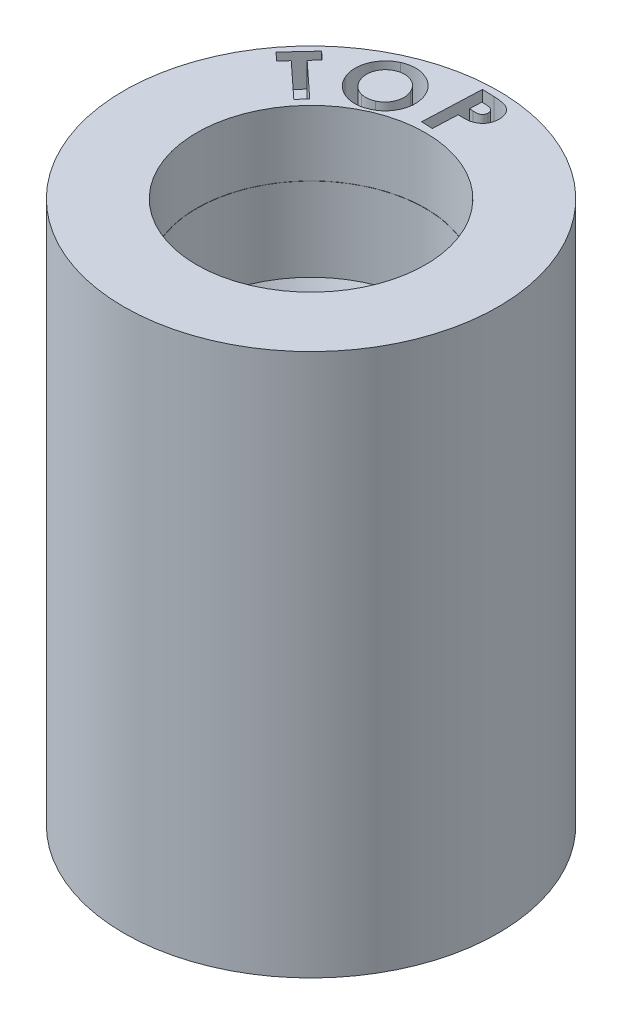
SolidWorks part; units mm, degrees
ref_plane "Front Plane" through (0, 0, 0) normal (0, 0, 1) x (1, 0, 0)
ref_plane "Top Plane" through (0, 0, 0) normal (0, 1, 0) x (1, 0, 0)
ref_plane "Right Plane" through (0, 0, 0) normal (1, 0, 0) x (0, 0, -1)
sketch "Sketch1" plane through (0, 0, 0) normal (0, 0, 1) x (1, 0, 0)
  line L0 (-5.7256, 16.593) -> (-5.7256, 0)
  line L1 (-5.7256, 0) -> (-2.5, 0)
  line L2 (-2.5, 0) -> (-2.5, 1)
  line L3 (-2.5, 1) -> (-4.7256, 1) construction
  line L4 (-4.7256, 1) -> (-4.7256, 4) construction
  line L5 (-4.7256, 4) -> (-1.9155, 1.1898) construction
  line L6 (-1.9155, 1.1898) -> (-4.7256, 7.007) construction
  line L7 (-4.7256, 7.007) -> (-4.7256, 8.007) construction
  line L8 (-4.7256, 8.007) -> (-2.0655, 5.3468) construction
  line L9 (-2.0655, 5.3468) -> (-4.7256, 10.8535) construction
  line L10 (-4.7256, 10.8535) -> (-4.7256, 11.8535) construction
  line L11 (-4.7256, 11.8535) -> (-2.1655, 9.2933) construction
  line L12 (-4.7256, 8.007) -> (-4.7256, 10.8535) construction
  line L13 (-4.7256, 4) -> (-4.7256, 7.007) construction
  line L14 (-2.1655, 9.2933) -> (-4.7256, 14.593) construction
  line L15 (-4.7256, 14.593) -> (-4.7256, 16.593) construction
  line L16 (-2.85, 2.1244) -> (-2.85, 3.1244)
  line L17 (-3, 6.2814) -> (-3, 7.2814)
  line L18 (-3.1, 10.2279) -> (-3.1, 11.2279)
  line L19 (-3.1, 10.2279) -> (-4.7256, 11.8535) construction
  line L20 (-4.7256, 11.8535) -> (-4.7256, 14.593) construction
  line L21 (-5.7256, 16.593) -> (-4.7256, 16.593)
  line L22 (-3.1, 11.2279) -> (-4.7256, 14.593) construction
  line L23 (-4.7256, 8.007) -> (-3, 6.2814) construction
  line L24 (-3, 7.2814) -> (-4.7256, 10.8535) construction
  line L25 (-4.7256, 7.007) -> (-2.85, 3.1244) construction
  line L26 (-2.85, 2.1244) -> (-4.7256, 4) construction
  line L27 (-3.1, 10.2279) -> (-3.6686, 8.6655)
  line L28 (-3.6686, 8.6655) -> (-3, 7.2814)
  line L29 (-3, 6.2814) -> (-3.5909, 4.658)
  line L30 (-3.5909, 4.658) -> (-2.85, 3.1244)
  line L31 (-2.85, 2.1244) -> (-3.2592, 1)
  line L32 (-3.2592, 1) -> (-2.5, 1)
  line L33 (-4.7256, 16.593) -> (-3.5, 16.593)
  line L34 (-3.5, 16.593) -> (-3.5, 14.593)
  line L35 (-3.5, 14.593) -> (-4.7256, 14.593) construction
  line L36 (-3.1, 11.2279) -> (-3.4937, 12.0429)
  line L37 (-3.4937, 12.0429) -> (-3.4937, 14.593)
  line L38 (-3.4937, 14.593) -> (-3.5, 14.593)
  dimension "D3" = 1
  dimension "D2" = 45
  dimension "D4" = 45
  dimension "D5" = 45
  dimension "D1" = 1
  dimension "D9" = 2.5
  dimension "D10" = 1
  dimension "D6" = 3.1
  dimension "D7" = 3
  dimension "D8" = 2.85
  dimension "D11" = 1
  dimension "D12" = 3
  dimension "D13" = 2
  dimension "D14" = 200
  dimension "D15" = 3.5
ref_axis "Axis1" through (0, 31.7469, 0) along (0, -1, 0)
revolve "Revolve1" add sketch "Sketch1" angle 360 about axis through (0, 31.7469, 0) along (0, -1, 0)
sketch "Sketch2" plane through (0, 16.593, 0) normal (0, 1, 0) x (1, 0, 0)
  arc A0 (-3.1309, 2.1162) -> (3.3228, 1.7999) centre (0, 0) cw construction
  text T0 "TOP" font "Century Gothic" height 1.8
extrude "Cut-Extrude1" cut sketch "Sketch2" against normal blind 1
equation "\"angle\"=45"
equation "\"D2@Sketch1\"=\"angle\""
equation "\"D4@Sketch1\"=\"angle\""
equation "\"D5@Sketch1\"=\"angle\""
